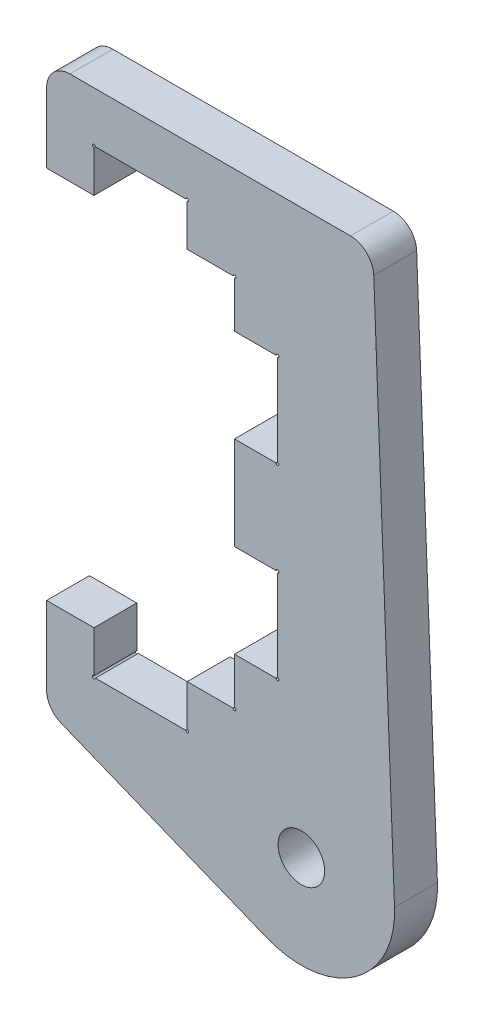
SolidWorks part; units mm, degrees
ref_plane "Front Plane" through (0, 0, 0) normal (0, 0, 1) x (1, 0, 0)
ref_plane "Top Plane" through (0, 0, 0) normal (0, 1, 0) x (1, 0, 0)
ref_plane "Right Plane" through (0, 0, 0) normal (1, 0, 0) x (0, 0, -1)
sketch "Sketch1" plane through (0, 0, 0) normal (0, 0, 1) x (1, 0, 0)
  line L0 (21.9055, -38.504) -> (12.8, -25.5) construction
  line L1 (-12.8, -25.5) -> (-6.35, -25.5)
  line L2 (-12.8, -25.5) -> (-12.8, -38.2)
  line L3 (-12.8, 25.5) -> (-6.35, 25.5)
  line L4 (12.8, -25.5) -> (12.8, -19.05)
  line L5 (-12.8, -25.5) -> (12.8, 25.5) construction
  line L6 (-12.8, 25.5) -> (12.8, -25.5) construction
  line L7 (12.8, 0) -> (-12.8, 0) construction
  line L8 (6.35, 31.342) -> (-6.35, 31.342)
  line L9 (31.65, 38.2) -> (-12.8, 38.2)
  line L11 (17.8082, -29.3382) -> (-12.8, 21.0875) construction
  line L12 (31.65, 38.2) -> (-10.1206, -12.2151) construction
  line L13 (-12.8, -38.2) -> (17.155, -50.2821)
  line L14 (31.65, 38.2) -> (34.596, -38.0135)
  line L15 (6.35, 31.342) -> (6.35, 25.5)
  line L16 (18.642, 19.05) -> (12.8, 19.05)
  line L17 (-6.35, 31.342) -> (-6.35, 25.5)
  line L18 (6.35, 31.342) -> (-6.35, 25.5) construction
  line L19 (6.35, 25.5) -> (-6.35, 31.342) construction
  line L20 (0, -25.5) -> (0, 25.5) construction
  line L21 (6.35, 25.5) -> (12.8, 25.5)
  line L25 (12.8, 19.05) -> (12.8, 25.5)
  line L28 (18.642, 6.35) -> (12.8, 6.35)
  line L29 (18.642, 6.35) -> (18.642, 19.05)
  line L34 (18.642, -6.35) -> (12.8, -6.35)
  line L35 (18.642, -6.35) -> (18.642, -19.05)
  line L36 (18.642, -19.05) -> (12.8, -19.05)
  line L37 (6.35, -31.342) -> (6.35, -25.5)
  line L38 (-6.35, -31.342) -> (-6.35, -25.5)
  line L39 (6.35, -31.342) -> (-6.35, -31.342)
  line L41 (6.35, -25.5) -> (12.8, -25.5)
  line L42 (12.8, -6.35) -> (12.8, 6.35)
  line L43 (-12.8, 38.2) -> (-12.8, 25.5)
  circle A0 centre (21.9055, -38.504) radius 3.175
  arc A1 (17.155, -50.2821) -> (34.596, -38.0135) centre (21.9055, -38.504) ccw
  point P0 (0, 0)
  point P6 (0, 0)
  point P13 (0, 28.421)
  point P33 (15.721, 12.7)
  dimension "D5" = 6.35
  dimension "D6" = 25.4
  dimension "D1" = 25.6
  dimension "D2" = 51
  dimension "D3" = 12.7
  dimension "D4" = 12.7
  dimension "D7" = 145
  dimension "D8" = 15.875
  dimension "D9" = 12.7
  dimension "D10" = 5.842
  dimension "D11" = 44.45
extrude "Boss-Extrude1" add sketch "Sketch1" along normal blind 5.842
fillet "Fillet2" radius 3.175 3 edges at (-12.8, 38.2, 2.921) (-12.8, -38.2, 2.921) (31.65, 38.2, 2.921)
sketch "Sketch2" plane through (0, 0, 5.842) normal (0, 0, 1) x (1, 0, 0)
  line L0 (12.8, 0) -> (-12.8, 0) construction
  line L1 (12.8, 6.35) -> (12.8, -6.35) construction
  circle A0 centre (-6.35, 31.342) radius 0.1984
  circle A1 centre (6.35, 31.342) radius 0.1984
  circle A2 centre (12.8, 25.5) radius 0.1984
  circle A3 centre (18.642, 6.35) radius 0.1984
  circle A4 centre (18.642, 19.05) radius 0.1984
  circle A5 centre (18.642, -19.05) radius 0.1984
  circle A6 centre (18.642, -6.35) radius 0.1984
  circle A7 centre (12.8, -25.5) radius 0.1984
  circle A8 centre (6.35, -31.342) radius 0.1984
  circle A9 centre (-6.35, -31.342) radius 0.1984
  dimension "D1" = 0.3969
  dimension "D2" = 0.3969
  dimension "D3" = 0.3969
  dimension "D4" = 0.3969
  dimension "D5" = 0.3969
extrude "Cut-Extrude1" cut sketch "Sketch2" against normal through all
